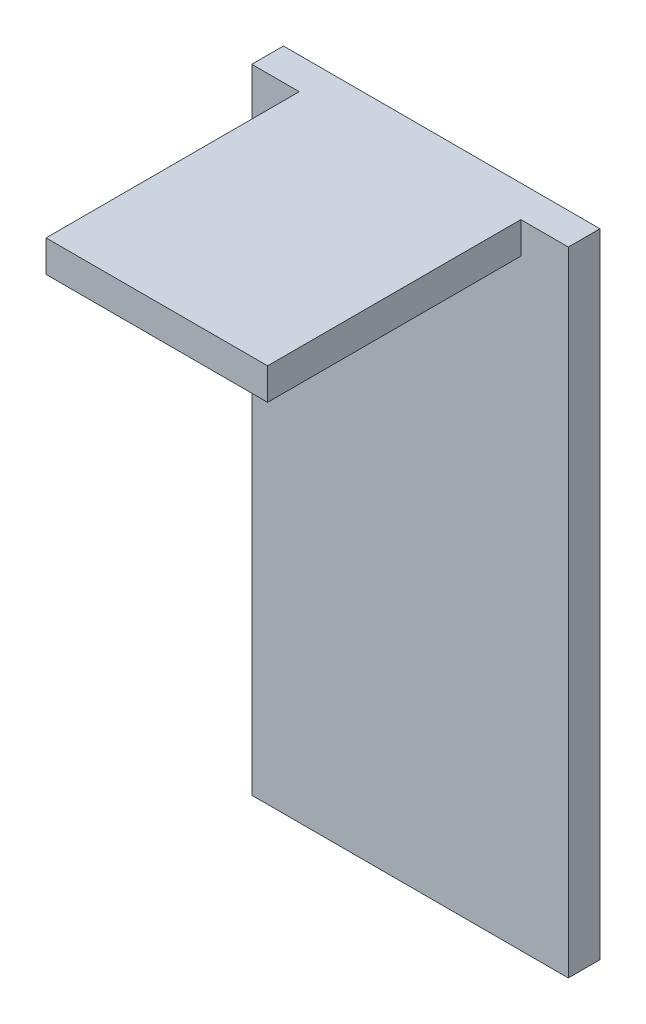
SolidWorks part; units mm, degrees
ref_plane "Front Plane" through (0, 0, 0) normal (0, 0, 1) x (1, 0, 0)
ref_plane "Top Plane" through (0, 0, 0) normal (0, 1, 0) x (1, 0, 0)
ref_plane "Right Plane" through (0, 0, 0) normal (1, 0, 0) x (0, 0, -1)
sketch "Sketch1" plane through (0, 0, 0) normal (0, 1, 0) x (1, 0, 0)
  line L1 (0, 0) -> (35, 0)
  line L2 (0, 0) -> (0, 40)
  line L3 (0, 40) -> (35, 40)
  line L4 (35, 0) -> (35, 40)
  dimension "D1" = 40
  dimension "D2" = 35
extrude "Boss-Extrude1" add sketch "Sketch1" along normal blind 5
sketch "Sketch4" plane through (0, 5, 0) normal (0, 1, 0) x (1, 0, 0)
  line L0 (17.5, 45.2831) -> (17.5, -2.9631) construction
  line L1 (35, 0) -> (35, 40) construction
  line L2 (0, 40) -> (0, 0) construction
sketch "Sketch5" plane through (0, 5, 0) normal (0, 1, 0) x (1, 0, 0)
  line L0 (-7.5, 45) -> (42.5, 45)
  line L1 (42.5, 45) -> (42.5, 40)
  line L2 (42.5, 40) -> (-7.5, 40)
  line L3 (-7.5, 40) -> (-7.5, 45)
  line L4 (35, 40) -> (0, 40) construction
  line L5 (17.5, 45.2831) -> (17.5, -2.9631) construction
  dimension "D1" = 50
  dimension "D2" = 5
  dimension "D3" = 25
extrude "Boss-Extrude2" add sketch "Sketch5" against normal blind 100
